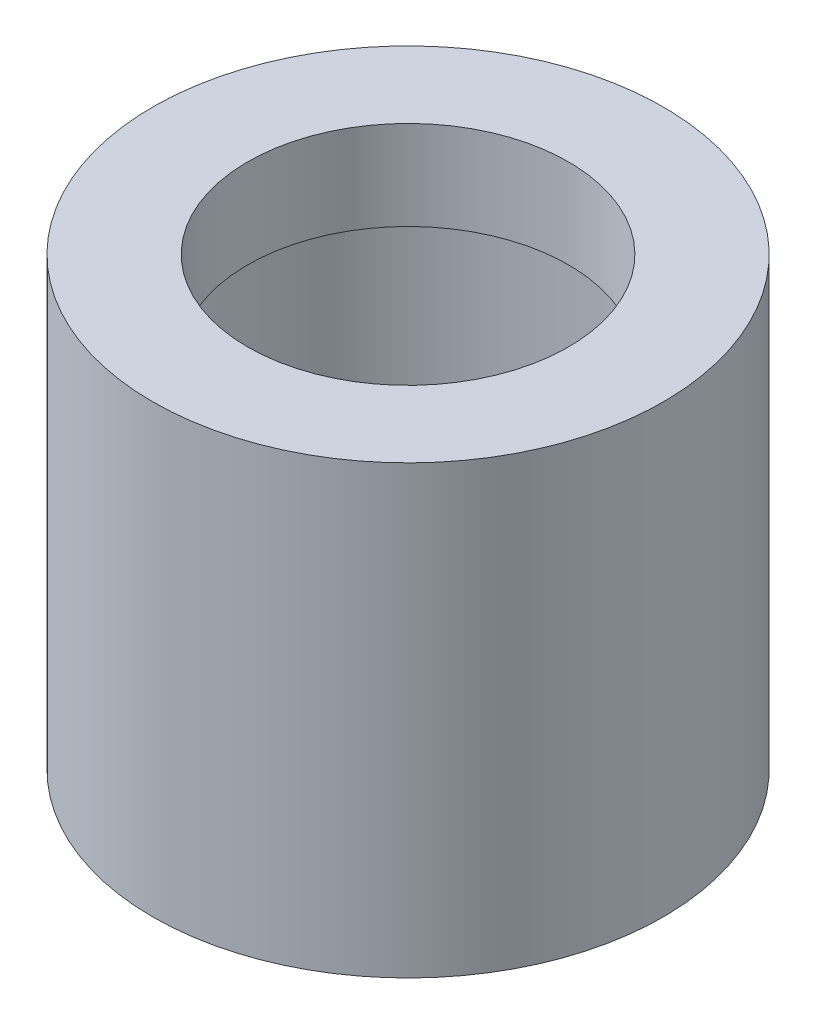
SolidWorks part; units mm, degrees
ref_plane "Front Plane" through (0, 0, 0) normal (0, 0, 1) x (1, 0, 0)
ref_plane "Top Plane" through (0, 0, 0) normal (0, 1, 0) x (1, 0, 0)
ref_plane "Right Plane" through (0, 0, 0) normal (1, 0, 0) x (0, 0, -1)
sketch "Sketch1" plane through (0, 0, 0) normal (0, 1, 0) x (1, 0, 0)
  circle A0 centre (0, 0) radius 10.9
  circle A1 centre (0, 0) radius 13.45
extrude "Boss-Extrude1" add sketch "Sketch1" along normal blind 18.8
sketch "Sketch3" plane through (0, 18.8, 0) normal (0, 1, 0) x (1, 0, 0)
  circle A0 centre (0, 0) radius 13.45
  circle A1 centre (0, 0) radius 8.45
extrude "Boss-Extrude2" add sketch "Sketch3" along normal blind 4.7
